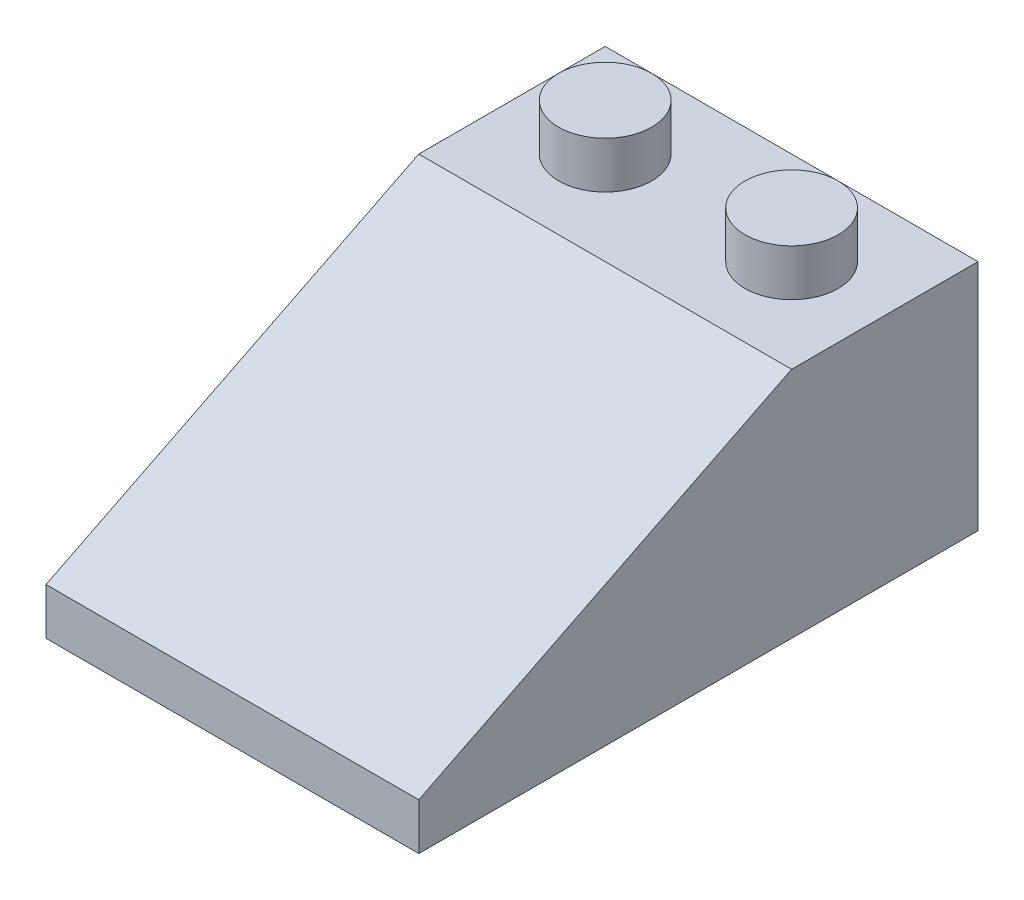
SolidWorks part; units mm, degrees
ref_plane "Front Plane" through (0, 0, 0) normal (0, 0, 1) x (1, 0, 0)
ref_plane "Top Plane" through (0, 0, 0) normal (0, 1, 0) x (1, 0, 0)
ref_plane "Right Plane" through (0, 0, 0) normal (1, 0, 0) x (0, 0, -1)
sketch "Sketch1" plane through (0, 0, 0) normal (1, 0, 0) x (0, 0, -1)
  line L0 (-24, 0) -> (0, 0)
  line L1 (0, 0) -> (0, 10)
  line L2 (0, 10) -> (-8, 10)
  line L3 (-8, 10) -> (-24, 2)
  line L4 (-24, 2) -> (-24, 0)
  dimension "D1" = 24
  dimension "D2" = 10
  dimension "D3" = 8
  dimension "D4" = 2
extrude "Boss-Extrude1" add sketch "Sketch1" along normal blind 16
sketch "Sketch2" plane through (0, 10, 0) normal (0, 1, 0) x (1, 0, 0)
  line L0 (8, 0) -> (8, -8) construction
  line L1 (16, 0) -> (0, 0) construction
  line L2 (16, -8) -> (0, -8) construction
  line L3 (0, 0) -> (0, -8) construction
  circle A0 centre (4, -4) radius 2
  circle A1 centre (12, -4) radius 2
  dimension "D1" = 4
  dimension "D2" = 4
  dimension "D3" = 4
extrude "Boss-Extrude2" add sketch "Sketch2" along normal blind 2
shell "Shell3" thickness 1
sketch "Sketch3" plane through (0, 0, 0) normal (0, -1, 0) x (1, 0, 0)
  line L0 (8, 1) -> (8, 8) construction
  line L1 (15, 1) -> (1, 1) construction
  line L2 (16, 0) -> (0, 0) construction
  line L3 (1, 12) -> (15, 12) construction
  line L4 (1, 23) -> (1, 1) construction
  line L5 (15, 23) -> (15, 1) construction
  circle A0 centre (8, 8) radius 2.7
  circle A1 centre (8, 8) radius 1.7
  circle A2 centre (8, 16) radius 1.7
  circle A3 centre (8, 16) radius 2.7
  dimension "D1" = 5.4
  dimension "D2" = 3.4
  dimension "D3" = 8
extrude "Boss-Extrude3" add sketch "Sketch3" against normal up to next
